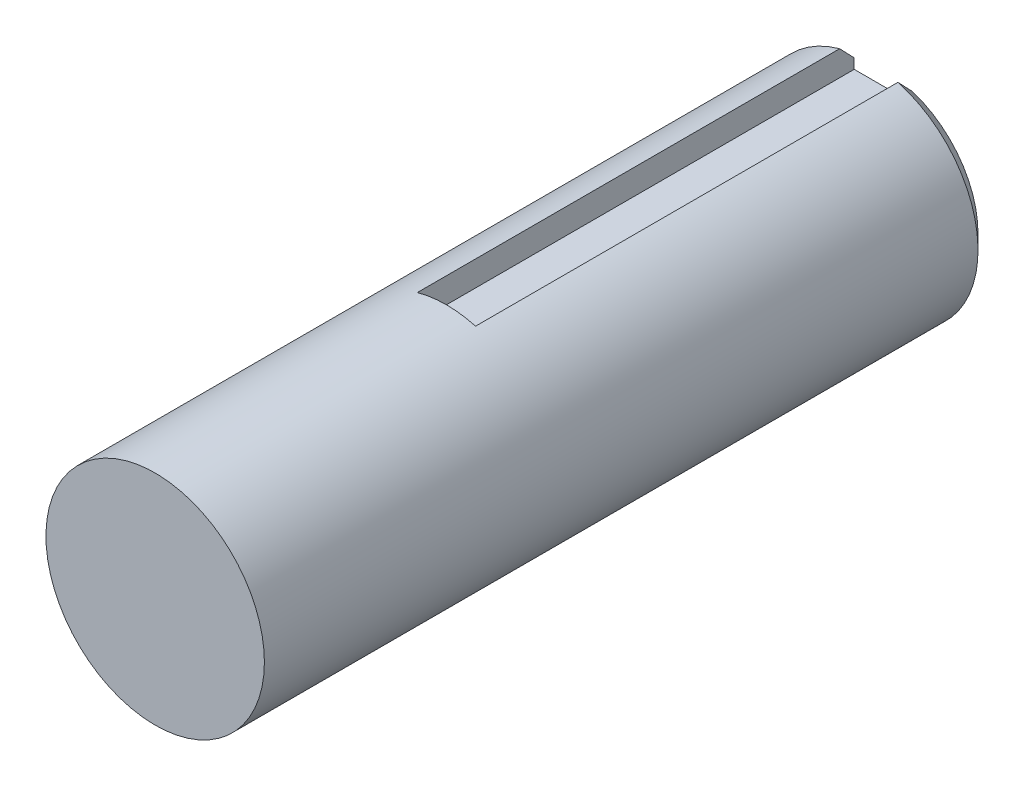
SolidWorks part; units mm, degrees
material "AISI 4130 Steel, normalized at 870C"
ref_plane "Front Plane" through (0, 0, 0) normal (0, 0, 1) x (1, 0, 0)
ref_plane "Top Plane" through (0, 0, 0) normal (0, 1, 0) x (1, 0, 0)
ref_plane "Right Plane" through (0, 0, 0) normal (1, 0, 0) x (0, 0, -1)
sketch "Sketch1" plane through (0, 0, 0) normal (0, 0, 1) x (1, 0, 0)
  circle A0 centre (0, 0) radius 15
extrude "Boss-Extrude1" add sketch "Sketch1" along normal blind 100
chamfer "Chamfer1" distance 2 angle 45 1 edges at (15, 0, 0)
sketch "Sketch2" plane through (0, 0, 100) normal (0, 0, 1) x (1, 0, 0)
  line L0 (0, 0) -> (0, 15)
  circle A0 centre (0, 0) radius 15 construction
ref_plane "Plane1" through (0, 15, 100) normal (0, 1, 0) x (1, 0, 0)
sketch "Sketch3" plane through (0, 15, 100) normal (0, 1, 0) x (1, 0, 0)
  line L0 (13, 100) -> (-13, 100) construction
  line L1 (-4, 100) -> (4, 100)
  line L2 (-4, 100) -> (-4, 40)
  line L3 (-4, 40) -> (4, 40)
  line L4 (4, 100) -> (4, 40)
  line L5 (0, 0) -> (0, 98) construction
  dimension "D1" = 4
extrude "Cut-Extrude1" cut sketch "Sketch3" against normal blind 4
fillet "Fillet1" radius 3 1 edges at (0, 11, 60)
